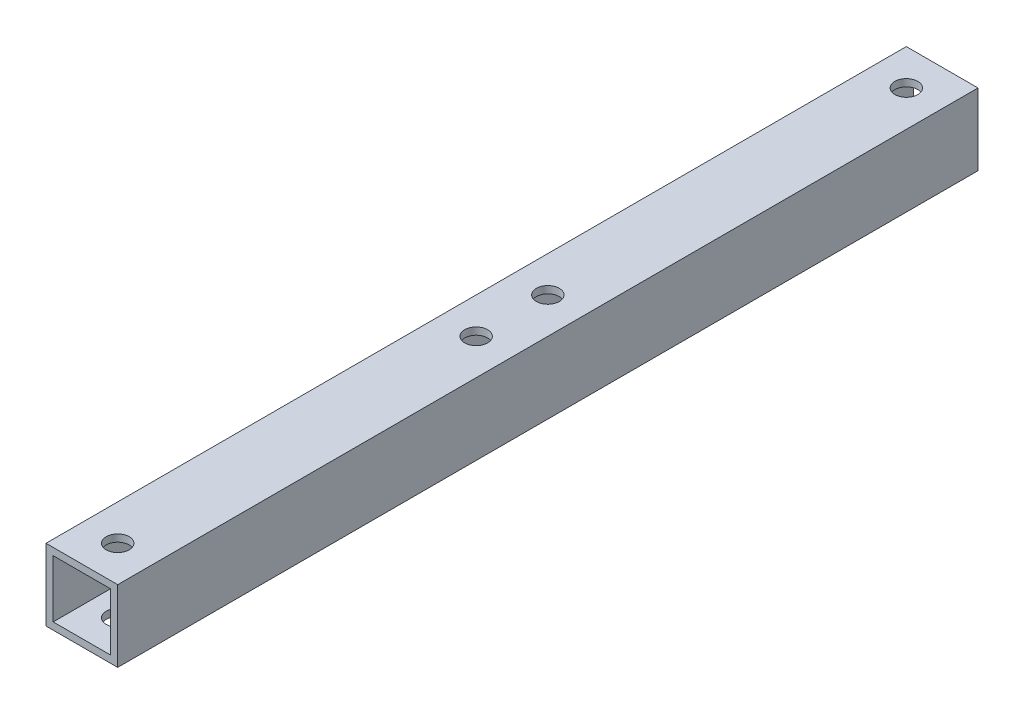
SolidWorks part; units mm, degrees
material "6061 合金"
ref_plane "正面" through (0, 0, 0) normal (0, 0, 1) x (1, 0, 0)
ref_plane "平面" through (0, 0, 0) normal (0, 1, 0) x (1, 0, 0)
ref_plane "右側面" through (0, 0, 0) normal (1, 0, 0) x (0, 0, -1)
sketch "断面 スケッチ" plane through (0, 0, 0) normal (0, 0, 1) x (1, 0, 0)
  line L1 (-5, -5) -> (5, -5)
  line L2 (-5, -5) -> (-5, 5)
  line L3 (-5, 5) -> (5, 5)
  line L4 (5, -5) -> (5, 5)
  line L5 (-5, -5) -> (5, 5) construction
  line L6 (-5, 5) -> (5, -5) construction
  point P0 (0, 0)
  dimension "D1" = 10
extrude "フレーム全長" add sketch "断面 スケッチ" along normal blind 120 thin thin type one direction reverse wall 1
sketch "上面穴 スケッチ" plane through (0, 5, 0) normal (0, 1, 0) x (1, 0, 0)
  line L0 (0, 0) -> (0, -120) construction
  line L1 (5, 0) -> (-5, 0) construction
  line L2 (5, -120) -> (-5, -120) construction
  line L3 (-5, -60) -> (5, -60) construction
  line L4 (-5, -120) -> (-5, 0) construction
  line L5 (5, -120) -> (5, 0) construction
  circle A0 centre (0, -5) radius 1.6
  circle A1 centre (0, -55) radius 1.6
  circle A2 centre (0, -115) radius 1.6
  circle A3 centre (0, -65) radius 1.6
  dimension "D1" = 5
  dimension "D2" = 3.2
  dimension "D3" = 50
sketch "側面穴 スケッチ" plane through (5, 0, 0) normal (1, 0, 0) x (0, 0, -1)
  line L0 (0, 0) -> (-120, 0) construction
  line L1 (0, -5) -> (0, 5) construction
  line L2 (-120, -5) -> (-120, 5) construction
  line L3 (-60, 5) -> (-60, -5) construction
  line L4 (-120, 5) -> (0, 5) construction
  line L5 (-120, -5) -> (0, -5) construction
  circle A0 centre (-15, 0) radius 1.6
  dimension "D1" = 15
  dimension "D2" = 3.2
extrude "上面穴貫通" cut sketch "上面穴 スケッチ" against normal through all
extrude "側面穴貫通" [suppressed] cut sketch "側面穴 スケッチ" against normal through all
fillet "フィレット" [suppressed] radius 5
